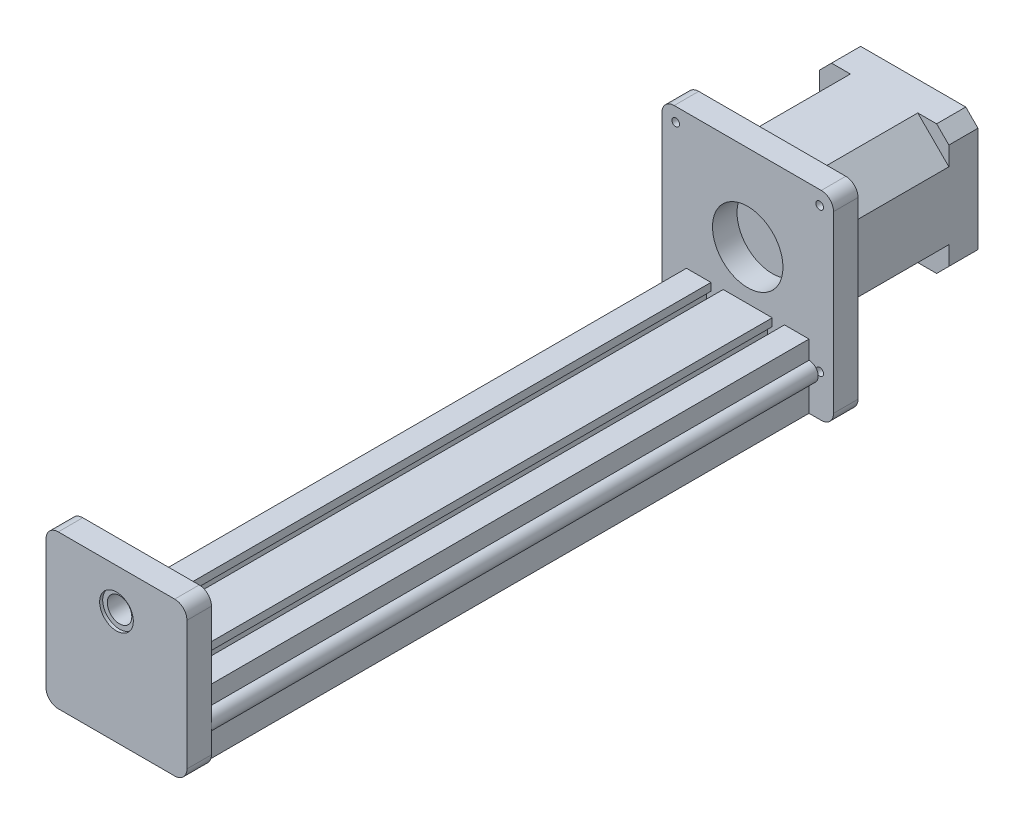
SolidWorks part; units mm, degrees
ref_plane "Front Plane" through (0, 0, 0) normal (0, 0, 1) x (1, 0, 0)
ref_plane "Top Plane" through (0, 0, 0) normal (0, 1, 0) x (1, 0, 0)
ref_plane "Right Plane" through (0, 0, 0) normal (1, 0, 0) x (0, 0, -1)
sketch "Sketch2" plane through (0, 0, 0) normal (0, 0, 1) x (1, 0, 0)
  line L0 (0, 37) -> (0, 65) construction
  line L1 (-28, 0) -> (28, 0)
  line L2 (-28, 0) -> (-28, 65)
  line L3 (-28, 65) -> (28, 65)
  line L4 (28, 0) -> (28, 65)
  line L5 (0, 37) -> (-28, 37) construction
  line L7 (23.5, 13.5) -> (-23.5, 13.5) construction
  line L8 (23.5, 13.5) -> (23.5, 60.5) construction
  line L9 (23.5, 60.5) -> (-23.5, 60.5) construction
  line L10 (-23.5, 13.5) -> (-23.5, 60.5) construction
  line L11 (23.5, 13.5) -> (-23.5, 60.5) construction
  line L12 (23.5, 60.5) -> (-23.5, 13.5) construction
  circle A0 centre (0, 37) radius 11.5
  point P4 (0, 0)
  point P15 (23.5, 60.5)
  point P16 (-23.5, 60.5)
  point P17 (-23.5, 13.5)
  point P18 (23.5, 13.5)
  dimension "D3" = 23
  dimension "D1" = 56
  dimension "D2" = 65
  dimension "D4" = 47
extrude "Boss-Extrude2" add sketch "Sketch2" against normal blind 8
sketch "Sketch1" plane through (0, 0, 0) normal (0, 0, 1) x (1, 0, 0)
  line L0 (8, 0) -> (-8, 0)
  line L1 (-8, 0) -> (-8, 2.5)
  line L2 (-8, 2.5) -> (-6.5, 2.5)
  line L3 (-6.5, 2.5) -> (-6.5, 6.5)
  line L4 (-6.5, 6.5) -> (-13.5, 6.5)
  line L5 (-13.5, 6.5) -> (-13.5, 2.5)
  line L6 (-13.5, 2.5) -> (-12, 2.5)
  line L7 (-12, 2.5) -> (-12, 0)
  line L8 (-12, 0) -> (-20, 0)
  line L9 (-20, 0) -> (-20, 9)
  line L10 (-12, 0) -> (-8, 0) construction
  line L11 (-10, 0) -> (-10, 6.5) construction
  line L12 (-20, 15) -> (-20, 21)
  line L13 (-20, 21) -> (-12, 21)
  line L14 (-12, 21) -> (-12, 18.5)
  line L15 (-12, 18.5) -> (-13.5, 18.5)
  line L16 (-13.5, 18.5) -> (-13.5, 14.5)
  line L17 (-13.5, 14.5) -> (-6.5, 14.5)
  line L18 (-6.5, 14.5) -> (-6.5, 18.5)
  line L19 (-6.5, 18.5) -> (-8, 18.5)
  line L20 (-8, 18.5) -> (-8, 21)
  line L21 (-8, 21) -> (8, 21)
  line L22 (0, 21) -> (0, 0) construction
  line L23 (10, 0) -> (10, 6.5) construction
  line L24 (12, 0) -> (8, 0) construction
  line L25 (8, 18.5) -> (8, 21)
  line L26 (6.5, 18.5) -> (8, 18.5)
  line L27 (6.5, 14.5) -> (6.5, 18.5)
  line L28 (13.5, 14.5) -> (6.5, 14.5)
  line L29 (13.5, 18.5) -> (13.5, 14.5)
  line L30 (12, 18.5) -> (13.5, 18.5)
  line L31 (12, 21) -> (12, 18.5)
  line L32 (20, 21) -> (12, 21)
  line L33 (20, 15) -> (20, 21)
  line L34 (20, 0) -> (20, 9)
  line L35 (12, 0) -> (20, 0)
  line L36 (12, 2.5) -> (12, 0)
  line L37 (13.5, 2.5) -> (12, 2.5)
  line L38 (13.5, 6.5) -> (13.5, 2.5)
  line L39 (6.5, 6.5) -> (13.5, 6.5)
  line L40 (6.5, 2.5) -> (6.5, 6.5)
  line L41 (8, 2.5) -> (6.5, 2.5)
  line L42 (8, 0) -> (8, 2.5)
  line L43 (-10, 6.5) -> (-10, 14.5) construction
  line L44 (-12, 21) -> (-8, 21) construction
  line L45 (-10, 21) -> (-10, 14.5) construction
  arc A0 (-20, 9) -> (-20, 15) centre (-20, 12) ccw
  arc A1 (20, 9) -> (20, 15) centre (20, 12) cw
  point P4 (0, 0)
  dimension "D1" = 21
  dimension "D2" = 9
  dimension "D3" = 6
  dimension "D4" = 40
  dimension "D5" = 20
  dimension "D6" = 4
  dimension "D7" = 6.5
  dimension "D8" = 7
  dimension "D9" = 4
extrude "Boss-Extrude1" add sketch "Sketch1" along normal blind 198 separate body
sketch "Sketch3" plane through (0, 0, 198) normal (0, 0, 1) x (1, 0, 0)
  line L0 (-8, 0) -> (8, 0) construction
  line L1 (-23, 0) -> (23, 0)
  line L2 (-23, 0) -> (-23, 50)
  line L3 (-23, 50) -> (23, 50)
  line L4 (23, 0) -> (23, 50)
  circle A0 centre (0, 37) radius 5.5
  point P4 (0, 0)
  point P7 (0, 0)
  dimension "D3" = 11
  dimension "D1" = 46
  dimension "D2" = 50
extrude "Boss-Extrude3" add sketch "Sketch3" along normal blind 8 separate body
ref_plane "Plane1" through (0, 0, 205) normal (0, 0, 1) x (1, 0, 0)
sketch "Sketch4" plane through (0, 0, 205) normal (0, 0, 1) x (1, 0, 0)
  circle A1 centre (0, 37) radius 5.5 construction
  circle A2 centre (0, 37) radius 5.5
  circle A3 centre (0, 37) radius 4
  dimension "D1" = 8
extrude "Boss-Extrude4" add sketch "Sketch4" against normal blind 6 separate body
fillet "Fillet1" radius 4 4 edges at (28, 0, -4) (-28, 0, -4) (28, 65, -4) (-28, 65, -4)
fillet "Fillet2" radius 4 4 edges at (23, 0, 202) (-23, 0, 202) (23, 50, 202) (-23, 50, 202)
sketch "Sketch5" plane through (0, 0, 0) normal (0, 0, 1) x (1, 0, 0)
  circle A0 centre (-20, 12) radius 3
  circle A1 centre (20, 12) radius 3
  arc A2 (20, 15) -> (20, 9) centre (20, 12) ccw construction
  arc A3 (-20, 9) -> (-20, 15) centre (-20, 12) ccw construction
extrude "Boss-Extrude5" add sketch "Sketch5" along normal up to surface (198 mm away) separate body up to face at (0, 25, 198)
sketch "Sketch6" plane through (0, 0, -8) normal (0, 0, -1) x (-1, 0, 0)
  line L1 (-21.15, 15.85) -> (21.15, 15.85)
  line L2 (-21.15, 15.85) -> (-21.15, 58.15)
  line L3 (-21.15, 58.15) -> (21.15, 58.15)
  line L4 (21.15, 15.85) -> (21.15, 58.15)
  line L5 (-21.15, 15.85) -> (21.15, 58.15) construction
  line L6 (-21.15, 58.15) -> (21.15, 15.85) construction
  point P0 (0, 37)
  dimension "D1" = 42.3
extrude "Boss-Extrude6" add sketch "Sketch6" along normal blind 6.5
sketch "Sketch7" plane through (0, 0, -14.5) normal (0, 0, -1) x (-1, 0, 0)
  line L1 (-11, 58.15) -> (-21.15, 48)
  line L2 (-21.15, 48) -> (-21.15, 26)
  line L3 (-21.15, 26) -> (-11, 15.85)
  line L4 (-11, 15.85) -> (11, 15.85)
  line L5 (11, 15.85) -> (21.15, 26)
  line L6 (21.15, 26) -> (21.15, 48)
  line L7 (21.15, 48) -> (11, 58.15)
  line L8 (11, 58.15) -> (-11, 58.15)
  line L9 (21.15, 58.15) -> (-21.15, 58.15) construction
  line L10 (-21.15, 15.85) -> (21.15, 15.85) construction
  line L11 (-21.15, 58.15) -> (-21.15, 15.85) construction
  line L12 (21.15, 15.85) -> (21.15, 58.15) construction
  point P10 (0, 58.15)
  point P11 (0, 58.15)
  point P14 (0, 15.85)
  point P15 (0, 15.85)
  point P18 (-21.15, 37)
  point P19 (-21.15, 37)
  point P21 (21.15, 37)
  point P24 (21.15, 37)
  dimension "D1" = 135
  dimension "D2" = 22
extrude "Boss-Extrude7" add sketch "Sketch7" along normal blind 30
sketch "Sketch8" plane through (0, 0, -44.5) normal (0, 0, -1) x (-1, 0, 0)
  line L0 (21.15, 26) -> (21.15, 48) construction
  line L1 (-21.15, 15.85) -> (21.15, 15.85)
  line L2 (-21.15, 15.85) -> (-21.15, 58.15)
  line L3 (-21.15, 58.15) -> (21.15, 58.15)
  line L4 (21.15, 15.85) -> (21.15, 58.15)
  line L5 (11, 58.15) -> (-11, 58.15) construction
  point P4 (21.15, 37)
  point P7 (21.15, 37)
  point P10 (0, 58.15)
  point P11 (0, 58.15)
extrude "Boss-Extrude8" add sketch "Sketch8" along normal blind 9.5
chamfer "Chamfer1" distance 4 angle 45 8 edges at (-21.15, 15.85, -49.25) (-21.15, 15.85, -11.25) (-21.15, 58.15, -11.25) (-21.15, 58.15, -49.25) (21.15, 15.85, -49.25) (21.15, 15.85, -11.25) (21.15, 58.15, -49.25) (21.15, 58.15, -11.25)
hole_wizard "Tap Drill for M3x0.5 Tap1" positions "Sketch10" profile "Sketch11" hole size "M3x0.5" standard "ANSI Metric" end condition through all
sketch "Sketch10" plane through (0, 0, 0) normal (0, 0, 1) x (1, 0, 0)
  point P0 (23.5, 60.5)
  point P3 (-23.5, 60.5)
  point P6 (-23.5, 13.5)
  point P9 (23.5, 13.5)
sketch "Sketch11" plane through (23.5, 60.5, 0) normal (1, 0, 0) x (0, -1, 0)
  line L0 (0, 0) -> (0, 54)
  line L1 (0, 54) -> (1.25, 54)
  line L2 (1.25, 54) -> (1.25, 0)
  line L5 (1.25, 0) -> (0, 0)
  line L11 (0, -6.35) -> (0, 107.95) construction
  dimension "Thru Hole Dia." = 2.5
  dimension "Thru Hole Depth" = 54
